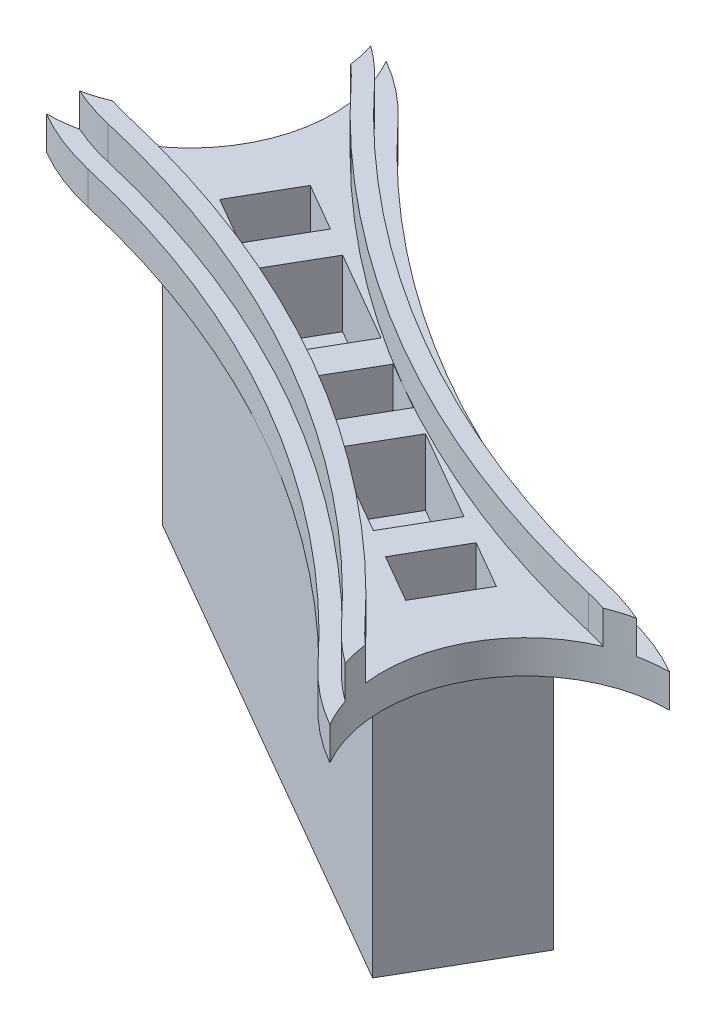
SolidWorks part; units mm, degrees
ref_plane "Front Plane" through (0, 0, 0) normal (0, 0, 1) x (1, 0, 0)
ref_plane "Top Plane" through (0, 0, 0) normal (0, 1, 0) x (1, 0, 0)
ref_plane "Right Plane" through (0, 0, 0) normal (1, 0, 0) x (0, 0, -1)
sketch "Sketch3" plane through (0, 0, 0) normal (0, 1, 0) x (1, 0, 0)
  line L0 (46.0055, 47.735) -> (-3.4393, 76.282) construction
  line L7 (4.3956, 71.7585) -> (1.3956, 66.5624) construction
  line L10 (35.1706, 47.0624) -> (38.1706, 52.2585) construction
  line L11 (1.3956, 66.5624) -> (35.1706, 47.0624) construction
  arc A28 (-14.6977, 69.782) -> (-3.4393, 89.282) centre (-14.6977, 82.782) ccw
  arc A29 (-14.6977, 69.782) -> (-8.4794, 67.3367) centre (-3.4393, 89.282) ccw
  arc A30 (40.7786, 38.8976) -> (-8.4794, 67.3367) centre (-30.1706, -27.1119) ccw
  arc A31 (40.7786, 38.8976) -> (46.0055, 34.735) centre (57.2638, 54.235) ccw
  arc A32 (57.2638, 54.235) -> (46.0055, 34.735) centre (57.2638, 41.235) ccw
  arc A33 (51.0455, 56.6804) -> (57.2638, 54.235) centre (46.0055, 34.735) cw
  arc A34 (51.0455, 56.6804) -> (1.7875, 85.1195) centre (72.7368, 151.129) cw
  arc A35 (-3.4393, 89.282) -> (1.7875, 85.1195) centre (-14.6977, 69.782) cw
  circle A36 centre (-14.6977, 82.782) radius 13
  circle A37 centre (57.2638, 41.235) radius 13
extrude "Boss-Extrude1" add sketch "Sketch3" along normal blind 3 contours A28 A36 | A35 A28 A29 A30 A31 A32 A33 A34 | A32 A37
sketch "Sketch10" plane through (0, 3, 0) normal (0, 1, 0) x (1, 0, 0)
  arc A8 (-5.6712, 87.0859) -> (-13.9117, 72.813) centre (-14.6977, 82.782) ccw
  arc A9 (-13.9117, 72.813) -> (-7.8079, 70.2606) centre (-3.4393, 89.282) ccw
  arc A10 (42.975, 40.9411) -> (-7.8079, 70.2606) centre (-30.1706, -27.1119) ccw
  arc A11 (42.975, 40.9411) -> (48.2374, 36.9312) centre (57.2638, 54.235) ccw
  arc A12 (48.2374, 36.9312) -> (56.4779, 51.2041) centre (57.2638, 41.235) ccw
  arc A13 (56.4779, 51.2041) -> (50.374, 53.7565) centre (46.0055, 34.735) ccw
  arc A14 (-0.4089, 83.076) -> (50.374, 53.7565) centre (72.7368, 151.129) ccw
  arc A15 (-0.4089, 83.076) -> (-5.6712, 87.0859) centre (-14.6977, 69.782) ccw
  arc A16 (-4.5454, 88.184) -> (-14.2997, 71.2889) centre (-14.6977, 82.782) ccw
  arc A17 (-14.2997, 71.2889) -> (-8.1436, 68.7986) centre (-3.4393, 89.282) ccw
  arc A18 (41.8768, 39.9193) -> (-8.1436, 68.7986) centre (-30.1706, -27.1119) ccw
  arc A19 (41.8768, 39.9193) -> (47.1115, 35.8331) centre (57.2638, 54.235) ccw
  arc A20 (47.1115, 35.8331) -> (56.8659, 52.7281) centre (57.2638, 41.235) ccw
  arc A21 (56.8659, 52.7281) -> (50.7098, 55.2184) centre (46.0055, 34.735) ccw
  arc A22 (0.6893, 84.0977) -> (50.7098, 55.2184) centre (72.7368, 151.129) ccw
  arc A23 (0.6893, 84.0977) -> (-4.5454, 88.184) centre (-14.6977, 69.782) ccw
  arc A24 (-4.5454, 88.184) -> (-14.2997, 71.2889) centre (-14.6977, 82.782) ccw
  arc A25 (-14.2997, 71.2889) -> (-8.1436, 68.7986) centre (-3.4393, 89.282) ccw
  arc A26 (41.8768, 39.9193) -> (-8.1436, 68.7986) centre (-30.1706, -27.1119) ccw
  arc A27 (41.8768, 39.9193) -> (47.1115, 35.8331) centre (57.2638, 54.235) ccw
  arc A28 (47.1115, 35.8331) -> (56.8659, 52.7281) centre (57.2638, 41.235) ccw
  arc A29 (56.8659, 52.7281) -> (50.7098, 55.2184) centre (46.0055, 34.735) ccw
  arc A30 (0.6893, 84.0977) -> (50.7098, 55.2184) centre (72.7368, 151.129) ccw
  arc A31 (0.6893, 84.0977) -> (-4.5454, 88.184) centre (-14.6977, 69.782) ccw
  arc A40 (-3.4393, 89.282) -> (-14.6977, 69.782) centre (-14.6977, 82.782) ccw
  arc A41 (-14.6977, 69.782) -> (-8.4794, 67.3367) centre (-3.4393, 89.282) ccw
  arc A42 (40.7786, 38.8976) -> (-8.4794, 67.3367) centre (-30.1706, -27.1119) ccw
  arc A43 (40.7786, 38.8976) -> (46.0055, 34.735) centre (57.2638, 54.235) ccw
  arc A44 (46.0055, 34.735) -> (57.2638, 54.235) centre (57.2638, 41.235) ccw
  arc A45 (57.2638, 54.235) -> (51.0455, 56.6804) centre (46.0055, 34.735) ccw
  arc A46 (1.7875, 85.1195) -> (51.0455, 56.6804) centre (72.7368, 151.129) ccw
  arc A47 (1.7875, 85.1195) -> (-3.4393, 89.282) centre (-14.6977, 69.782) ccw
  arc A48 (-3.4393, 89.282) -> (-14.6977, 69.782) centre (-14.6977, 82.782) ccw construction
  arc A49 (-14.6977, 69.782) -> (-8.4794, 67.3367) centre (-3.4393, 89.282) ccw construction
  arc A50 (40.7786, 38.8976) -> (-8.4794, 67.3367) centre (-30.1706, -27.1119) ccw construction
  arc A51 (40.7786, 38.8976) -> (46.0055, 34.735) centre (57.2638, 54.235) ccw construction
  arc A52 (46.0055, 34.735) -> (57.2638, 54.235) centre (57.2638, 41.235) ccw construction
  arc A53 (57.2638, 54.235) -> (51.0455, 56.6804) centre (46.0055, 34.735) ccw construction
  arc A54 (1.7875, 85.1195) -> (51.0455, 56.6804) centre (72.7368, 151.129) ccw construction
  arc A55 (1.7875, 85.1195) -> (-3.4393, 89.282) centre (-14.6977, 69.782) ccw construction
  dimension "D1" = 1.5
  dimension "D2" = 1.5
  dimension "D3" = 0
extrude "Boss-Extrude4" add sketch "Sketch10" along normal blind 3
sketch "Sketch11" plane through (0, 3, 0) normal (0, 1, 0) x (1, 0, 0)
  circle A0 centre (-14.6977, 82.782) radius 13
  circle A1 centre (57.2638, 41.235) radius 13
  arc A2 (-3.4393, 89.282) -> (-14.6977, 69.782) centre (-14.6977, 82.782) ccw construction
  arc A3 (46.0055, 34.735) -> (57.2638, 54.235) centre (57.2638, 41.235) ccw construction
extrude "Cut-Extrude2" cut sketch "Sketch11" against normal mid plane 13
sketch "Sketch12" plane through (0, 0, 0) normal (0, -1, 0) x (1, 0, 0)
  line L0 (-3.4393, -76.282) -> (46.0055, -47.735) construction
  line L1 (18.2831, -56.8124) -> (24.2831, -67.2047) construction
  line L2 (-4.2336, -69.8124) -> (1.7664, -80.2047)
  line L3 (1.7664, -80.2047) -> (46.7997, -54.2047)
  line L4 (46.7997, -54.2047) -> (40.7997, -43.8124)
  line L5 (40.7997, -43.8124) -> (-4.2336, -69.8124)
  line L6 (2.8645, -76.1066) -> (42.7017, -53.1066)
  line L7 (42.7017, -53.1066) -> (39.7017, -47.9105)
  line L8 (39.7017, -47.9105) -> (-0.1355, -70.9105)
  line L9 (-0.1355, -70.9105) -> (2.8645, -76.1066)
  arc A0 (-3.4393, -89.282) -> (-14.6977, -69.782) centre (-14.6977, -82.782) ccw construction
  arc A1 (46.0055, -34.735) -> (57.2638, -54.235) centre (57.2638, -41.235) ccw construction
  arc A2 (-8.4794, -67.3367) -> (40.7786, -38.8976) centre (-30.1706, 27.1119) ccw construction
  arc A3 (51.0455, -56.6804) -> (1.7875, -85.1195) centre (72.7368, -151.129) ccw construction
  dimension "D1" = 57.094
  dimension "D2" = 12
  dimension "D3" = 52
  dimension "D4" = 3
extrude "Boss-Extrude5" add sketch "Sketch12" along normal blind 3
sketch "Sketch13" plane through (0, 0, 0) normal (0, -1, 0) x (1, 0, 0)
  line L4 (39.7017, -47.9105) -> (-0.1355, -70.9105)
  line L5 (-0.1355, -70.9105) -> (2.8645, -76.1066)
  line L6 (2.8645, -76.1066) -> (42.7017, -53.1066)
  line L7 (42.7017, -53.1066) -> (39.7017, -47.9105)
  line L8 (39.7017, -47.9105) -> (-0.1355, -70.9105)
  line L9 (-0.1355, -70.9105) -> (2.8645, -76.1066)
  line L10 (2.8645, -76.1066) -> (42.7017, -53.1066)
  line L11 (42.7017, -53.1066) -> (39.7017, -47.9105)
  dimension "D1" = 0
extrude "Cut-Extrude3" cut sketch "Sketch13" against normal blind 24
sketch "Sketch14" plane through (0, -3, 0) normal (0, -1, 0) x (1, 0, 0)
  line L4 (40.7997, -43.8124) -> (-4.2336, -69.8124)
  line L5 (-4.2336, -69.8124) -> (1.7664, -80.2047)
  line L6 (1.7664, -80.2047) -> (46.7997, -54.2047)
  line L7 (46.7997, -54.2047) -> (40.7997, -43.8124)
  line L8 (40.7997, -43.8124) -> (-4.2336, -69.8124)
  line L9 (-4.2336, -69.8124) -> (1.7664, -80.2047)
  line L10 (1.7664, -80.2047) -> (46.7997, -54.2047)
  line L11 (46.7997, -54.2047) -> (40.7997, -43.8124)
  dimension "D1" = 0
extrude "Boss-Extrude6" add sketch "Sketch14" along normal blind 3
sketch "Sketch15" plane through (0, -3, 0) normal (0, 1, 0) x (1, 0, 0)
  line L0 (6.7927, 66.9105) -> (9.7927, 72.1066)
  line L1 (22.7831, 64.6066) -> (2.8645, 76.1066) construction
  line L2 (19.7831, 59.4105) -> (22.7831, 64.6066) construction
  line L3 (32.7735, 51.9105) -> (35.7735, 57.1066)
  line L4 (42.7017, 53.1066) -> (2.8645, 76.1066)
  line L5 (2.8645, 76.1066) -> (-0.1355, 70.9105)
  line L6 (-0.1355, 70.9105) -> (39.7017, 47.9105)
  line L7 (39.7017, 47.9105) -> (42.7017, 53.1066)
  line L8 (42.7017, 53.1066) -> (2.8645, 76.1066) construction
  line L9 (2.8645, 76.1066) -> (-0.1355, 70.9105) construction
  line L10 (-0.1355, 70.9105) -> (39.7017, 47.9105) construction
  line L11 (39.7017, 47.9105) -> (42.7017, 53.1066) construction
  line L12 (18.0199, 67.3566) -> (15.0199, 62.1605)
  line L13 (24.5462, 56.6605) -> (27.5462, 61.8566)
  line L14 (4.1946, 68.4105) -> (7.1946, 73.6066)
  line L15 (38.3715, 55.6066) -> (35.3715, 50.4105)
  line L16 (20.618, 65.8566) -> (17.618, 60.6605)
  line L17 (24.9481, 63.3566) -> (21.9481, 58.1605)
  line L18 (7.1946, 73.6066) -> (9.7927, 72.1066) construction
  line L19 (4.1946, 68.4105) -> (6.7927, 66.9105) construction
  line L20 (18.0199, 67.3566) -> (20.618, 65.8566) construction
  line L21 (24.9481, 63.3566) -> (27.5462, 61.8566) construction
  line L22 (35.7735, 57.1066) -> (38.3715, 55.6066) construction
  line L23 (35.3715, 50.4105) -> (32.7735, 51.9105) construction
  line L24 (24.5462, 56.6605) -> (21.9481, 58.1605) construction
  line L25 (21.9481, 58.1605) -> (17.618, 60.6605)
  point P18 (8.2927, 69.5085)
  line M14 (42.7017, 53.1066) -> (2.8645, 76.1066)
  line M16 (-0.1355, 70.9105) -> (39.7017, 47.9105)
  dimension "D2" = 8
  dimension "D3" = 8
  dimension "D4" = 11
  dimension "D5" = 3
  dimension "D6" = 3
  dimension "D7" = 3
  dimension "D1" = 0
extrude "Boss-Extrude7" add sketch "Sketch15" along normal blind 6 contours L14 L0 M16 M14 | L16 L12 M14 M16 | L17 L13 M14 M16 | L15 L3 M14 M16
sketch "Sketch16" plane through (0, -3, 0) normal (0, 1, 0) x (1, 0, 0)
  line L0 (42.7017, 53.1066) -> (38.3715, 55.6066) construction
  line L1 (38.3715, 55.6066) -> (35.3715, 50.4105) construction
  line L2 (35.3715, 50.4105) -> (39.7017, 47.9105) construction
  line L3 (39.7017, 47.9105) -> (42.7017, 53.1066) construction
  line L4 (24.9481, 63.3566) -> (20.618, 65.8566) construction
  line L5 (20.618, 65.8566) -> (17.618, 60.6605) construction
  line L6 (17.618, 60.6605) -> (21.9481, 58.1605) construction
  line L7 (21.9481, 58.1605) -> (24.9481, 63.3566) construction
  line L8 (-0.1355, 70.9105) -> (4.1946, 68.4105) construction
  line L9 (4.1946, 68.4105) -> (7.1946, 73.6066) construction
  line L10 (7.1946, 73.6066) -> (2.8645, 76.1066) construction
  line L11 (2.8645, 76.1066) -> (-0.1355, 70.9105) construction
  line L12 (42.7017, 53.1066) -> (38.3715, 55.6066)
  line L13 (38.3715, 55.6066) -> (35.3715, 50.4105)
  line L14 (35.3715, 50.4105) -> (39.7017, 47.9105)
  line L15 (39.7017, 47.9105) -> (42.7017, 53.1066)
  line L16 (24.9481, 63.3566) -> (20.618, 65.8566)
  line L17 (20.618, 65.8566) -> (17.618, 60.6605)
  line L18 (17.618, 60.6605) -> (21.9481, 58.1605)
  line L19 (21.9481, 58.1605) -> (24.9481, 63.3566)
  line L20 (-0.1355, 70.9105) -> (4.1946, 68.4105)
  line L21 (4.1946, 68.4105) -> (7.1946, 73.6066)
  line L22 (7.1946, 73.6066) -> (2.8645, 76.1066)
  line L23 (2.8645, 76.1066) -> (-0.1355, 70.9105)
extrude "Cut-Extrude4" cut sketch "Sketch16" against normal blind 3
sketch "Sketch17" plane through (0, -6, 0) normal (0, -1, 0) x (1, 0, 0)
  line L0 (42.7017, -53.1066) -> (39.7017, -47.9105)
  line L1 (39.7017, -47.9105) -> (-0.1355, -70.9105)
  line L2 (-0.1355, -70.9105) -> (2.8645, -76.1066)
  line L3 (2.8645, -76.1066) -> (42.7017, -53.1066)
  line L4 (46.7997, -54.2047) -> (40.7997, -43.8124)
  line L5 (40.7997, -43.8124) -> (-4.2336, -69.8124)
  line L6 (-4.2336, -69.8124) -> (1.7664, -80.2047)
  line L7 (1.7664, -80.2047) -> (46.7997, -54.2047)
  line L8 (46.7997, -54.2047) -> (40.7997, -43.8124)
  line L9 (40.7997, -43.8124) -> (-4.2336, -69.8124)
  line L10 (-4.2336, -69.8124) -> (1.7664, -80.2047)
  line L11 (1.7664, -80.2047) -> (46.7997, -54.2047)
  dimension "D1" = 0
  dimension "D2" = 3
extrude "Boss-Extrude8" add sketch "Sketch17" along normal blind 12
sketch "Sketch18" plane through (0, -18, 0) normal (0, -1, 0) x (1, 0, 0)
  line L0 (-1.2336, -75.0085) -> (43.7997, -49.0085) construction
  line L4 (1.7664, -80.2047) -> (46.7997, -54.2047)
  line L5 (46.7997, -54.2047) -> (40.7997, -43.8124)
  line L6 (40.7997, -43.8124) -> (-4.2336, -69.8124)
  line L7 (-4.2336, -69.8124) -> (1.7664, -80.2047)
  line L8 (1.7664, -80.2047) -> (46.7997, -54.2047)
  line L9 (46.7997, -54.2047) -> (40.7997, -43.8124)
  line L10 (40.7997, -43.8124) -> (-4.2336, -69.8124)
  line L11 (-4.2336, -69.8124) -> (1.7664, -80.2047)
  line L21 (18.2831, -56.8124) -> (24.2831, -67.2047) construction
  circle A0 centre (21.2831, -62.0085) radius 2.5
  dimension "D2" = 5
  dimension "D1" = 0
extrude "Boss-Extrude9" [suppressed] add sketch "Sketch18" along normal blind 3
sketch "Sketch19" plane through (0, -18, 0) normal (0, -1, 0) x (1, 0, 0)
  line L0 (2.3155, -78.1556) -> (44.7507, -53.6556)
  line L1 (44.7507, -53.6556) -> (40.2507, -45.8614)
  line L2 (40.2507, -45.8614) -> (-2.1845, -70.3614)
  line L3 (-2.1845, -70.3614) -> (2.3155, -78.1556) construction
  line L4 (1.7664, -80.2047) -> (46.7997, -54.2047)
  line L5 (46.7997, -54.2047) -> (40.7997, -43.8124)
  line L6 (40.7997, -43.8124) -> (-4.2336, -69.8124)
  line L7 (-4.2336, -69.8124) -> (1.7664, -80.2047)
  line L8 (1.7664, -80.2047) -> (46.7997, -54.2047)
  line L9 (46.7997, -54.2047) -> (40.7997, -43.8124)
  line L10 (40.7997, -43.8124) -> (-4.2336, -69.8124)
  line L11 (-4.2336, -69.8124) -> (-3.4836, -71.1114)
  line L12 (-2.1845, -70.3614) -> (-3.4836, -71.1114)
  line L13 (2.3155, -78.1556) -> (1.0164, -78.9056)
  line L14 (1.0164, -78.9056) -> (1.7664, -80.2047)
  line L16 (-3.4836, -71.1114) -> (1.0164, -78.9056) construction
  line L17 (-4.2336, -69.8124) -> (1.7664, -80.2047) construction
  dimension "D1" = 0
  dimension "D2" = 1.5
extrude "Boss-Extrude10" add sketch "Sketch19" along normal blind 3
sketch "Sketch20" plane through (0, -21, 0) normal (0, -1, 0) x (1, 0, 0)
  line L0 (1.7664, -80.2047) -> (46.7997, -54.2047) construction
  line L1 (46.7997, -54.2047) -> (40.7997, -43.8124) construction
  line L2 (40.7997, -43.8124) -> (-4.2336, -69.8124) construction
  line L3 (1.7664, -80.2047) -> (46.7997, -54.2047)
  line L4 (46.7997, -54.2047) -> (40.7997, -43.8124)
  line L5 (40.7997, -43.8124) -> (-4.2336, -69.8124)
  line L6 (-4.2336, -69.8124) -> (1.7664, -80.2047)
  line L7 (42.7017, -53.1066) -> (39.7017, -47.9105) construction
  line L8 (2.8645, -76.1066) -> (42.7017, -53.1066) construction
  line L9 (39.7017, -47.9105) -> (-0.1355, -70.9105) construction
  line L10 (-0.1355, -70.9105) -> (2.8645, -76.1066) construction
  line L11 (42.7017, -53.1066) -> (39.7017, -47.9105)
  line L12 (2.8645, -76.1066) -> (42.7017, -53.1066)
  line L13 (39.7017, -47.9105) -> (-0.1355, -70.9105)
  line L14 (-0.1355, -70.9105) -> (2.8645, -76.1066)
extrude "Boss-Extrude11" add sketch "Sketch20" along normal blind 3
sketch "Sketch21" plane through (-33.4048, 0, -19.2863) normal (-0.866, 0, -0.5) x (-0.5, 0, 0.866)
  line L0 (-68.8425, -18) -> (-68.8425, -12)
  line L1 (-59.8425, -18) -> (-59.8425, -12)
  line L2 (-68.8425, -12) -> (-59.8425, -12)
  line L3 (-68.8425, -18) -> (-59.8425, -18)
  dimension "D1" = 6
extrude "Cut-Extrude5" cut sketch "Sketch21" against normal blind 5
